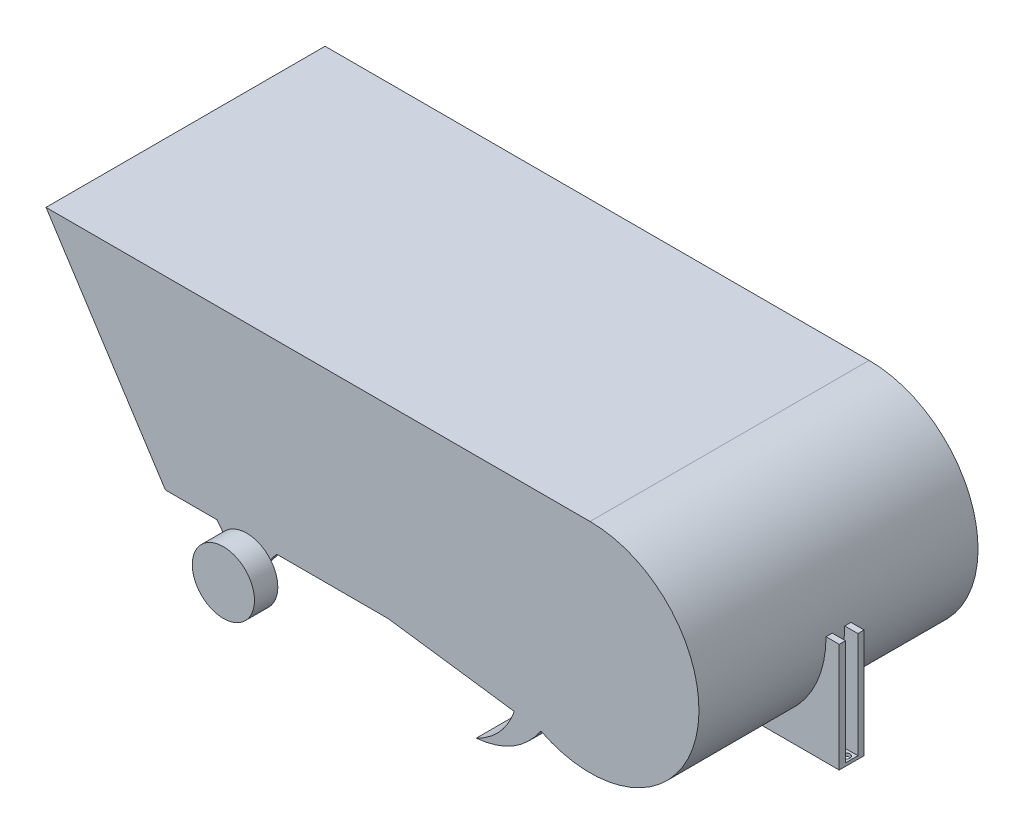
SolidWorks part; units mm, degrees
ref_plane "Front Plane" through (0, 0, 0) normal (0, 0, 1) x (1, 0, 0)
ref_plane "Top Plane" through (0, 0, 0) normal (0, 1, 0) x (1, 0, 0)
ref_plane "Right Plane" through (0, 0, 0) normal (1, 0, 0) x (0, 0, -1)
sketch "Sketch1" plane through (0, 0, 0) normal (0, 0, 1) x (1, 0, 0)
  line L0 (210.703, -28.5588) -> (401.2067, -56.8956)
  line L5 (-2242.2169, -200) -> (1757.7831, -200)
  line L6 (-2242.2169, -200) -> (-2242.2169, -300)
  line L7 (-2242.2169, -300) -> (1757.7831, -300)
  line L8 (1757.7831, -200) -> (1757.7831, -300)
  line L9 (446.0808, 244.7852) -> (96.6921, 60.9059) construction
  line L10 (446.0808, 244.7852) -> (446.0808, 698.7731) construction
  line L11 (446.0808, 244.7852) -> (-8.8424, 416.682) construction
  line L12 (0, 0) -> (-749.2179, 0) construction
  line L13 (-203.9454, 0) -> (-918.9979, 0)
  line L14 (-918.9979, 0) -> (-1302.6596, 594.7852)
  line L15 (-1302.6596, 594.7852) -> (446.0808, 594.7852)
  line L16 (160.7695, 352.5926) -> (-374.9932, 45)
  line L17 (-711.7066, 0) -> (-665.4604, 0)
  line L18 (-665.4604, 0) -> (-616.1336, 0)
  line L19 (446.0808, 549.7852) -> (-1220.0831, 549.7852)
  line L20 (-1220.0831, 549.7852) -> (-894.4752, 45)
  line L21 (-894.4752, 45) -> (-374.9932, 45)
  line L22 (796.0808, 501.4547) -> (796.0808, 45) construction
  line L23 (446.0808, 244.7852) -> (210.703, -28.5588) construction
  line L24 (-1302.6596, 594.7852) -> (796.0808, 594.7852)
  line L25 (-1302.6596, 594.7852) -> (-1302.6596, -200)
  line L26 (-1302.6596, -200) -> (796.0808, -200)
  line L27 (796.0808, 594.7852) -> (796.0808, -200)
  circle A0 centre (0, 0) radius 200
  circle A1 centre (446.0808, 244.7852) radius 300
  arc A2 (401.2067, -56.8956) -> (446.0808, 549.7852) centre (446.0808, 244.7852) ccw
  arc A4 (288.1927, -67.579) -> (446.0808, 594.7852) centre (446.0808, 244.7852) ccw
  arc A5 (160.7695, 352.5926) -> (176.1777, 102.7383) centre (446.0808, 244.7852) ccw
  arc A6 (176.1777, 102.7383) -> (-203.9454, 0) centre (0, 0) ccw
  circle A7 centre (-558.8658, 65) radius 265 construction
  spline S0 degree 2 poles (80.1156, -191.3842) (181.903, -142.415) (210.703, -28.5588) knots 0 0 0 1 1 1
  spline S1 degree 2 poles (80.1156, -191.3842) (212.0514, -178.8065) (288.1927, -67.579) knots 0 0 0 1 1 1
  dimension "D1" = 400
  dimension "D4" = 600
  dimension "D5" = 610
  dimension "D8" = 350
  dimension "D9" = 530
  dimension "D10" = 2098.7404
  dimension "D14" = 794.7852
  dimension "D2" = 100
  dimension "D3" = 4000
  dimension "D6" = 446.0808
  dimension "D7" = 244.7852
  dimension "D12" = 45
  dimension "D13" = 45
extrude "Boss-Extrude1" add sketch "Sketch1" along normal blind 897 contours S0 S1 A4 L15 L14 L13 A6 A5 L16 L21 L20 L19 A2 L0
sketch "Sketch2" plane through (0, 0, 897) normal (0, 0, 1) x (1, 0, 0)
  line L0 (-753.6185, 0) -> (-561.4717, 0)
  line L1 (-203.9454, 0) -> (-918.9979, 0) construction
  line L2 (-561.4717, 0) -> (-657.5451, -121.8018)
  line L3 (-657.5451, -121.8018) -> (-753.6185, 0)
  line L5 (-712.3704, -20) -> (-602.7198, -20)
  line L6 (-602.7198, -20) -> (-641.5875, -69.2764)
  line L7 (-673.5027, -69.2764) -> (-712.3704, -20)
  line L9 (-657.5451, -89.5075) -> (-712.3704, -20) construction
  line L11 (-602.7198, -20) -> (-657.5451, -89.5075) construction
  circle A0 centre (-657.5451, -89.5075) radius 10.767
  arc A1 (-641.5875, -69.2764) -> (-673.5027, -69.2764) centre (-657.5451, -89.5075) ccw
  circle A3 centre (-657.5451, -89.5075) radius 25.767 construction
  point P11 (-631.778, -89.5075)
  dimension "D1" = 20
  dimension "D2" = 15
extrude "Boss-Extrude2" add sketch "Sketch2" against normal blind 20
ref_plane "Plane1" through (0, 0, 448.5) normal (0, 0, 1) x (1, 0, 0)
mirror "Mirror1" about plane through (0, 0, 448.5) normal (0, 0, 1) of "Boss-Extrude2"
sketch "Sketch3" plane through (0, 0, 448.5) normal (0, 0, 1) x (1, 0, 0)
  line L7 (796.0808, -105.2148) -> (446.0808, -105.2148)
  line L8 (796.0808, 244.7852) -> (838.4442, 244.7852)
  line L9 (838.4442, 244.7852) -> (838.4442, -105.2148)
  line L10 (838.4442, -105.2148) -> (796.0808, -105.2148)
  arc A3 (288.1927, -67.579) -> (446.0808, 594.7852) centre (446.0808, 244.7852) ccw construction
  arc A4 (446.0808, -105.2148) -> (796.0808, 244.7852) centre (446.0808, 244.7852) ccw
extrude "Boss-Extrude3" add sketch "Sketch3" along normal blind 20 from offset 20
mirror "Mirror2" about plane through (0, 0, 448.5) normal (0, 0, 1) of bodies 104
sketch "Sketch4" plane through (0, -105.2148, 0) normal (0, -1, 0) x (1, 0, 0)
  line L0 (432.3932, 448.5) -> (-432.3932, 448.5) construction
  line L1 (838.4442, 408.5) -> (838.4442, 428.5) construction
  line L2 (788.4442, 473.5) -> (838.4442, 473.5)
  line L3 (788.4442, 473.5) -> (788.4442, 423.5)
  line L4 (788.4442, 423.5) -> (838.4442, 423.5)
  line L5 (838.4442, 473.5) -> (838.4442, 423.5)
  circle A1 centre (820.1689, 448.5) radius 12.5
  dimension "D1" = 50
  dimension "D2" = 25
  dimension "D3" = 50
  dimension "D4" = 25
  dimension "D5" = 0
extrude "Boss-Extrude4" add sketch "Sketch4" against normal blind 10
sketch "Sketch5" plane through (0, 0, 897) normal (0, 0, 1) x (1, 0, 0)
  circle A0 centre (-657.5451, -89.5075) radius 100
extrude "Boss-Extrude5" add sketch "Sketch5" along normal blind 75
mirror "Mirror3" about plane through (0, 0, 448.5) normal (0, 0, 1) of bodies 107
sketch "Sketch6" plane through (0, 0, 897) normal (0, 0, 1) x (1, 0, 0)
  line L0 (-203.9454, 0) -> (-561.4717, 0) construction
  line L1 (-753.6185, 0) -> (-918.9979, 0) construction
  line L2 (-918.9979, 0) -> (-1302.6596, 594.7852) construction
  line L3 (-1302.6596, 594.7852) -> (446.0808, 594.7852) construction
  line L4 (-203.9454, 0) -> (-561.4717, 0)
  line L5 (-753.6185, 0) -> (-918.9979, 0)
  line L6 (-918.9979, 0) -> (-1302.6596, 594.7852)
  line L7 (-1302.6596, 594.7852) -> (446.0808, 594.7852)
  line L8 (-753.6185, 0) -> (-561.4717, 0)
  line L9 (-203.9454, 0) -> (288.1927, -67.579)
  arc A0 (288.1927, -67.579) -> (446.0808, 594.7852) centre (446.0808, 244.7852) ccw construction
  arc A1 (288.1927, -67.579) -> (446.0808, 594.7852) centre (446.0808, 244.7852) ccw
extrude "Boss-Extrude6" add sketch "Sketch6" against normal blind 75
